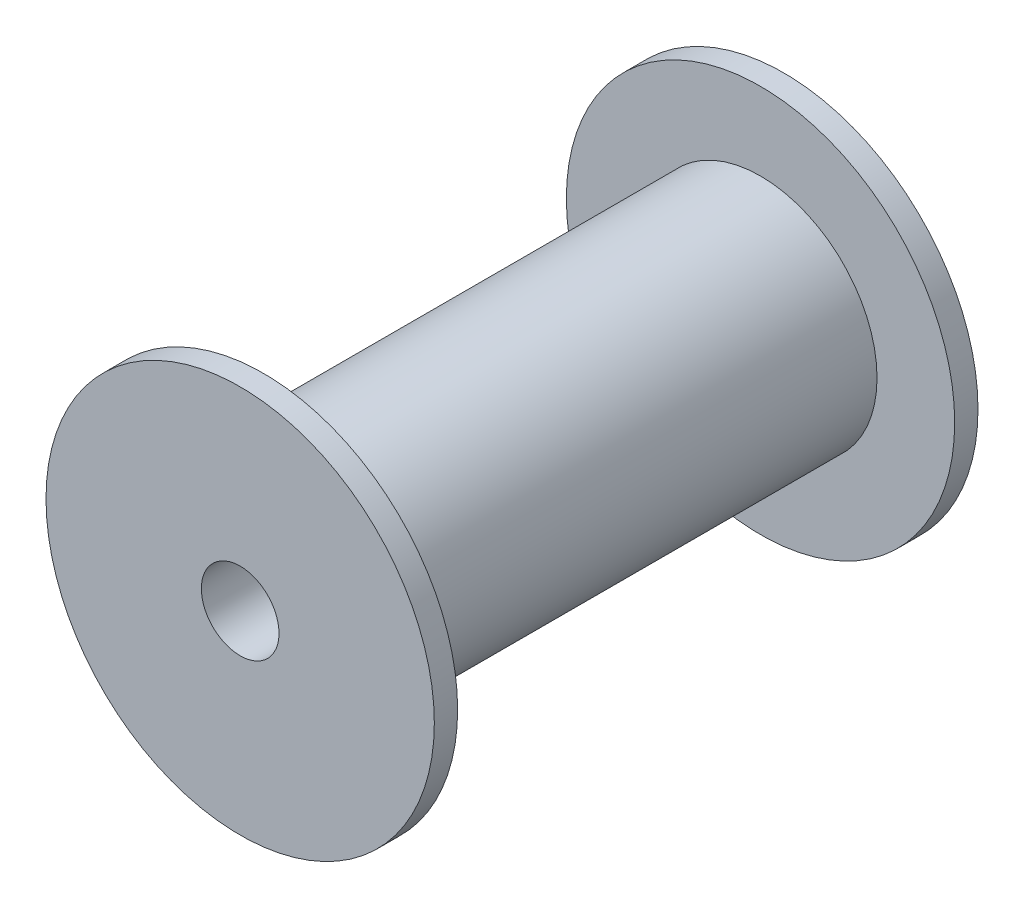
SolidWorks part; units mm, degrees
ref_plane "Alzado" through (0, 0, 0) normal (0, 0, 1) x (1, 0, 0)
ref_plane "Planta" through (0, 0, 0) normal (0, 1, 0) x (1, 0, 0)
ref_plane "Vista lateral" through (0, 0, 0) normal (1, 0, 0) x (0, 0, -1)
sketch3d "Sk_Cuerpo"
  line L0 (-425.1, 65, -50) -> (-425.1, 65, 25.5)
sweep "Cuerpo" add path "Sk_Cuerpo" circular profile diameter 30 parameters "D3"=30
sketch3d "Sk_Brida_izq"
  line L0 (-425.1, 65, -44.5) -> (-425.1, 65, -41.5)
sweep "Brida_izq" add path "Sk_Brida_izq" circular profile diameter 50 parameters "D3"=50
sketch3d "Sk_Brida_dcha"
  line L0 (-425.1, 65, 22.5) -> (-425.1, 65, 25.5)
sweep "Brida_dcha" add path "Sk_Brida_dcha" circular profile diameter 50 parameters "D3"=50
sketch3d "Sk_Taladro_eje"
  line L0 (-425.1, 65, -50) -> (-425.1, 65, 25.5)
sweep "Taladro_eje" cut path "Sk_Taladro_eje" circular profile diameter 10 parameters "D3"=10
sketch3d "Sk_Alojamiento_rodamiento_izq"
  line L0 (-425.1, 65, -50) -> (-425.1, 65, -42)
sweep "Alojamiento_rodamiento_izq" cut path "Sk_Alojamiento_rodamiento_izq" circular profile diameter 26 parameters "D3"=26
